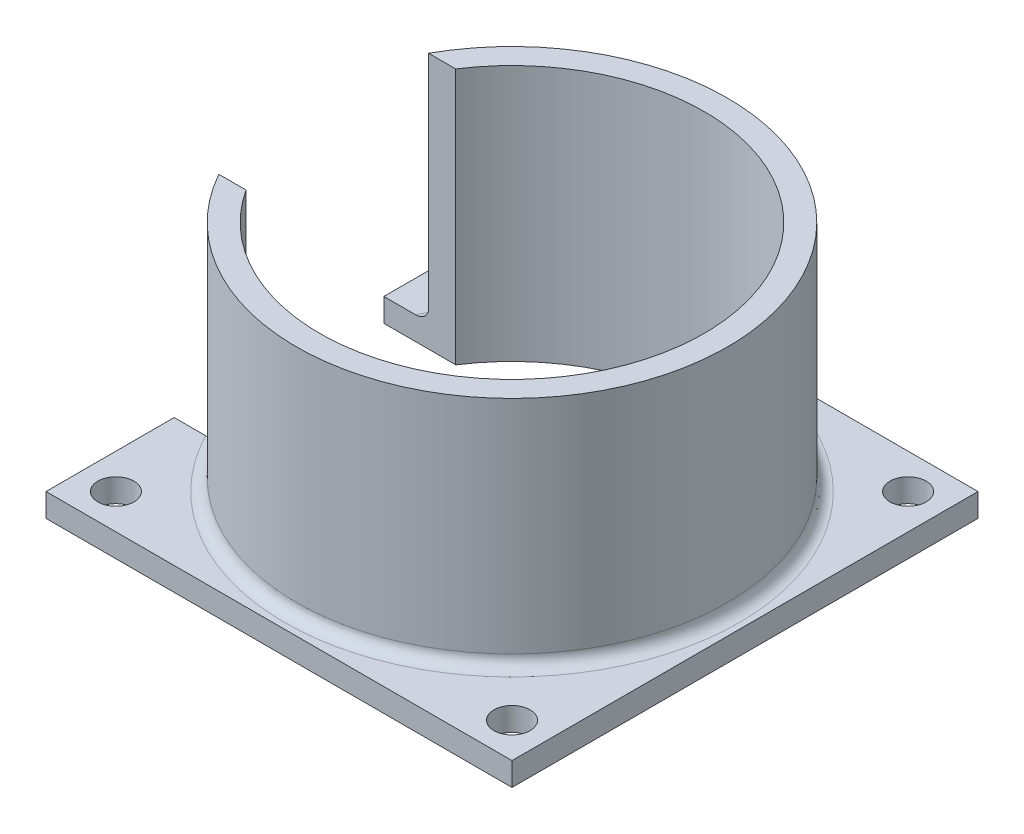
SolidWorks part; units mm, degrees
ref_plane "前视基准面" through (0, 0, 0) normal (0, 0, 1) x (1, 0, 0)
ref_plane "上视基准面" through (0, 0, 0) normal (0, 1, 0) x (1, 0, 0)
ref_plane "右视基准面" through (0, 0, 0) normal (1, 0, 0) x (0, 0, -1)
other "Configuration Table"
sketch "草图1" plane through (0, 0, 0) normal (0, 1, 0) x (1, 0, 0)
  line L0 (-20, 20) -> (20, 20)
  line L5 (-17, -17) -> (17, 17) construction
  line L6 (-17, 17) -> (17, -17) construction
  line L7 (20, -20) -> (20, 20)
  line L8 (-20, -20) -> (20, -20)
  line L9 (-20, -20) -> (-20, 20)
  circle A0 centre (-17, 17) radius 1.55
  circle A1 centre (17, 17) radius 1.55
  circle A2 centre (17, -17) radius 1.55
  circle A3 centre (-17, -17) radius 1.55
  circle A4 centre (0, 0) radius 16.5
  point P0 (0, 0)
  point P16 (0, 0)
  dimension "D3" = 3.1
  dimension "D5" = 33
  dimension "D1" = 34
  dimension "D2" = 34
  dimension "D4" = 4
extrude "凸台-拉伸1" add sketch "草图1" along normal blind 2
sketch "草图2" plane through (0, 2, 0) normal (0, 1, 0) x (1, 0, 0)
  circle A0 centre (0, 0) radius 16.5
  circle A1 centre (0, 0) radius 18.5
  dimension "D1" = 2
extrude "凸台-拉伸2" add sketch "草图2" along normal blind 20
fillet "圆角1" radius 1 1 edges at (0, 2, 18.5)
sketch "草图3" plane through (0, 0, 0) normal (0, -1, 0) x (1, 0, 0)
  line L0 (0, 0) -> (-16.5, 0)
  line L7 (-20.5, -9) -> (-12.5, -9)
  line L8 (-20.5, -9) -> (-20.5, 9)
  line L9 (-20.5, 9) -> (-12.5, 9)
  line L10 (-12.5, -9) -> (-12.5, 9)
  line L11 (-20.5, -9) -> (-12.5, 9) construction
  line L12 (-20.5, 9) -> (-12.5, -9) construction
  circle A1 centre (0, 0) radius 16.5 construction
  line M6 (-20, 20) -> (-20, -20)
  circle M12 centre (0, 0) radius 16.5
  dimension "D1" = 18
  dimension "D2" = 8
extrude "切除-拉伸1" cut sketch "草图3" against normal through all contours L9 L7 M6 M12
